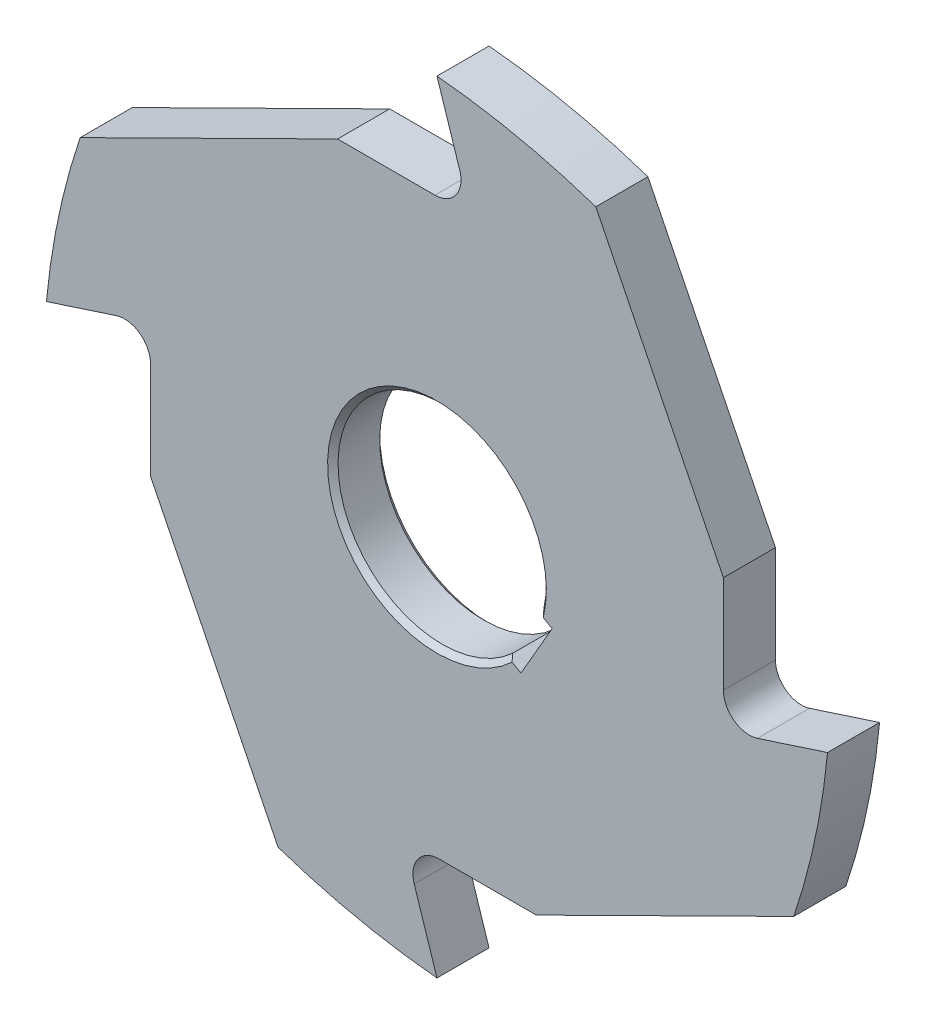
SolidWorks part; units mm, degrees
material "Cast Alloy Steel"
ref_plane "Front Plane" through (0, 0, 0) normal (0, 0, 1) x (1, 0, 0)
ref_plane "Top Plane" through (0, 0, 0) normal (0, 1, 0) x (1, 0, 0)
ref_plane "Right Plane" through (0, 0, 0) normal (1, 0, 0) x (0, 0, -1)
sketch "Sketch1" plane through (0, 0, 0) normal (0, 0, 1) x (1, 0, 0)
  line L0 (-55, 0) -> (55, 0) construction
  line L1 (0, -75) -> (0, 75) construction
  line L2 (-52.0911, 75) -> (52.0911, 75) construction
  line L3 (-52.0911, 55) -> (-50.9902, 55) construction
  line L6 (0, 75) -> (30.5052, 68.5159) construction
  line L8 (0, 55) -> (5, 55) construction
  line L9 (-0.3835, 55) -> (-20, 55)
  line L10 (0, 75) -> (4.3718, 61.5451)
  line L11 (55, -75) -> (55, 75) construction
  line L12 (-55, -75) -> (-55, 75) construction
  line L13 (6, 19.0788) -> (104, 19.0788) construction
  line L14 (55, 0) -> (55, 19.0788)
  line L15 (55, 19.0788) -> (30.5052, 68.5159)
  line L16 (5, -75) -> (5, 75) construction
  line L17 (-20, -75) -> (-20, 75) construction
  line L18 (-20, 55) -> (52.0911, 55) construction
  line L19 (-52.0911, 55) -> (52.0911, 55) construction
  line L20 (55, 0.3835) -> (55, 20)
  line L21 (75, 0) -> (61.5451, -4.3718)
  line L22 (19.0788, -55) -> (68.5159, -30.5052)
  line L23 (0, -55) -> (19.0788, -55)
  line L24 (0.3835, -55) -> (20, -55)
  line L25 (0, -75) -> (-4.3718, -61.5451)
  line L26 (-55, -19.0788) -> (-30.5052, -68.5159)
  line L27 (-55, 0) -> (-55, -19.0788)
  line L28 (-55, -0.3835) -> (-55, -20)
  line L29 (-75, 0) -> (-61.5451, 4.3718)
  line L30 (-19.0788, 55) -> (-68.5159, 30.5052)
  line L31 (0, 55) -> (-19.0788, 55)
  line L32 (13.5227, -14.7355) -> (16.1208, -16.2355)
  line L33 (22.1208, -5.8432) -> (16.1208, -16.2355)
  line L34 (19.5227, -4.3432) -> (22.1208, -5.8432)
  circle A0 centre (0, 0) radius 75
  arc A1 (6, 19.0788) -> (-19.5227, -4.3432) centre (0, 0) ccw
  arc A2 (-0.3835, 55) -> (4.3718, 61.5451) centre (-0.3835, 60) ccw
  arc A3 (0, 75) -> (30.5052, 68.5159) centre (-12.6276, -59.4081) cw
  arc A4 (55, 0.3835) -> (61.5451, -4.3718) centre (60, 0.3835) ccw
  arc A5 (75, 0) -> (68.5159, -30.5052) centre (-59.4081, 12.6276) cw
  arc A6 (0.3835, -55) -> (-4.3718, -61.5451) centre (0.3835, -60) ccw
  arc A7 (0, -75) -> (-30.5052, -68.5159) centre (12.6276, 59.4081) cw
  arc A8 (-55, -0.3835) -> (-61.5451, 4.3718) centre (-60, -0.3835) ccw
  arc A9 (-75, 0) -> (-68.5159, 30.5052) centre (59.4081, -12.6276) cw
  arc A10 (19.5227, -4.3432) -> (6, 19.0788) centre (0, 0) ccw
  arc A11 (-19.5227, -4.3432) -> (13.5227, -14.7355) centre (0, 0) ccw
  point P4 (0, 0)
  point P7 (0, 0)
  point P14 (0, 0)
  point P15 (0, 0)
  point P18 (0, 75)
  point P67 (0, 0)
  point P75 (0, 0)
  dimension "D1" = 150
  dimension "D2" = 40
  dimension "D7" = 5
  dimension "D12" = 135
  dimension "D13" = 5
  dimension "D3" = 12
  dimension "D4" = 3
  dimension "D5" = 6
  dimension "D6" = 20
  dimension "D8" = 60
  dimension "D9" = 18
  dimension "D10" = 55
  dimension "D16" = 30
  dimension "D17" = 60
  dimension "D18" = 4.3432
  dimension "D11" = 55
  dimension "D14" = 25
  dimension "D15" = 4
extrude "Boss-Extrude1" add sketch "Sketch1" against normal blind 10
chamfer "Chamfer1" distance 1 angle 45 2 edges at (-17.3205, 10, -10) (-17.3205, 10, 0)
